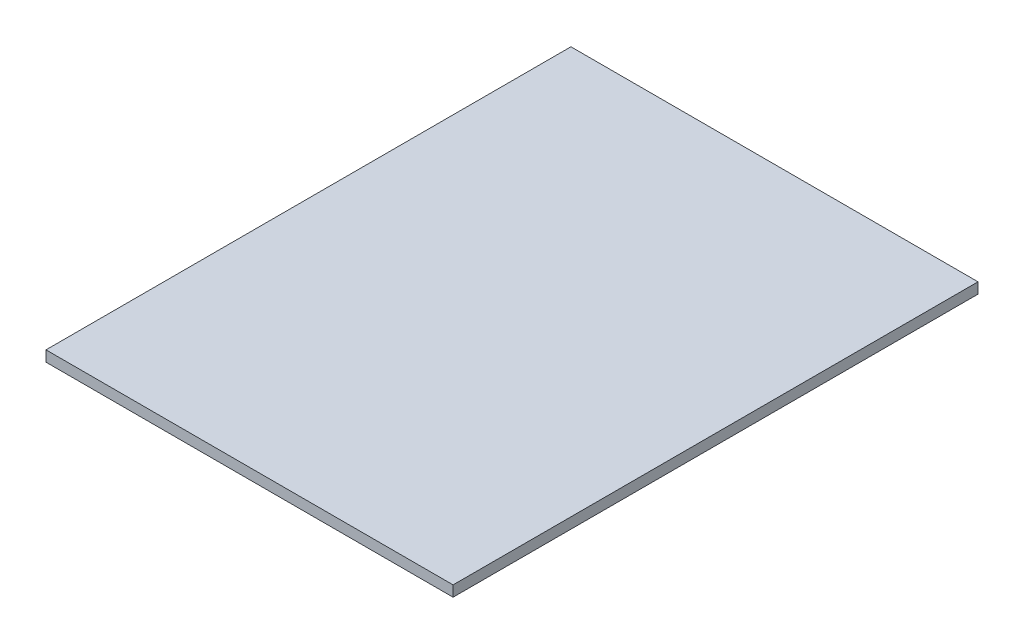
SolidWorks part; units mm, degrees
ref_plane "Front Plane" through (0, 0, 0) normal (0, 0, 1) x (1, 0, 0)
ref_plane "Top Plane" through (0, 0, 0) normal (0, 1, 0) x (1, 0, 0)
ref_plane "Right Plane" through (0, 0, 0) normal (1, 0, 0) x (0, 0, -1)
sketch "Sketch1" plane through (0, 0, 0) normal (0, 1, 0) x (1, 0, 0)
  line L1 (-241.3, -311.15) -> (241.3, -311.15)
  line L2 (-241.3, -311.15) -> (-241.3, 311.15)
  line L3 (-241.3, 311.15) -> (241.3, 311.15)
  line L4 (241.3, -311.15) -> (241.3, 311.15)
  line L5 (-241.3, -311.15) -> (241.3, 311.15) construction
  line L6 (-241.3, 311.15) -> (241.3, -311.15) construction
  point P0 (0, 0)
  dimension "D1" = 622.3
  dimension "D2" = 482.6
extrude "Boss-Extrude1" add sketch "Sketch1" along normal blind 12.7
